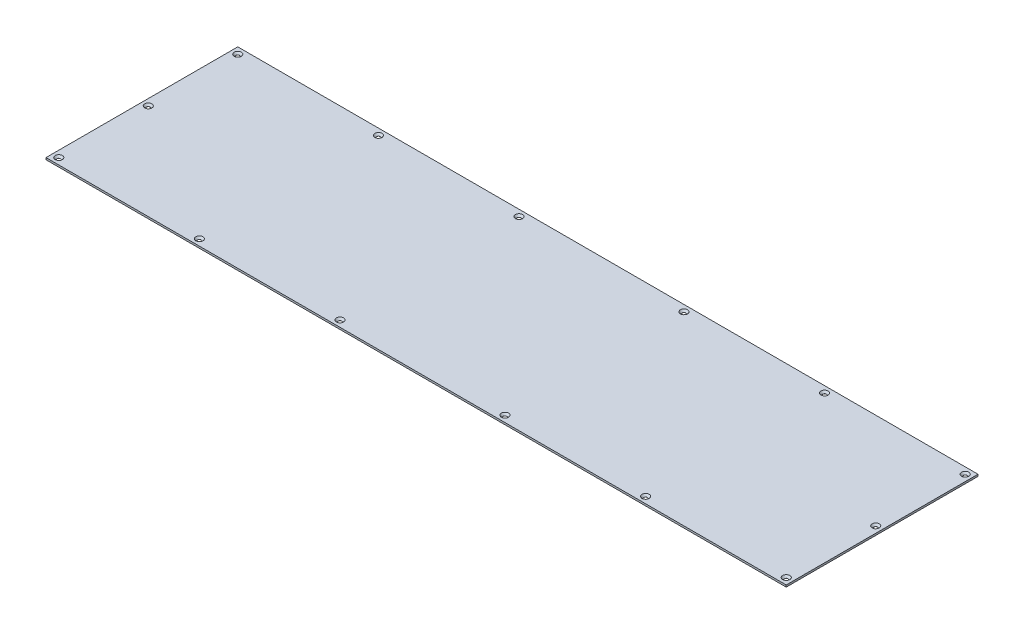
SolidWorks part; units mm, degrees
material "1060 Alloy"
ref_plane "Front Plane" through (0, 0, 0) normal (0, 0, 1) x (1, 0, 0)
ref_plane "Top Plane" through (0, 0, 0) normal (0, 1, 0) x (1, 0, 0)
ref_plane "Right Plane" through (0, 0, 0) normal (1, 0, 0) x (0, 0, -1)
sketch "Sketch1" plane through (0, 0, 0) normal (0, 1, 0) x (1, 0, 0)
  line L1 (-579, -150) -> (579, -150)
  line L2 (-579, -150) -> (-579, 150)
  line L3 (-579, 150) -> (579, 150)
  line L4 (579, -150) -> (579, 150)
  line L5 (-579, -150) -> (579, 150) construction
  line L6 (-579, 150) -> (579, -150) construction
  point P0 (0, 0)
  dimension "length" = 1158
  dimension "depth" = 300
extrude "Boss-Extrude1" add sketch "Sketch1" along normal blind 3
sketch "shelf profile projection" plane through (0, 3, 0) normal (0, 1, 0) x (1, 0, 0)
  line L0 (-579, -130) -> (-559, -150) construction
  line L1 (-579, -150) -> (-559, -150) construction
  line L2 (0, 0) -> (0, 50000) construction
  line L3 (0, 0) -> (50000, 0) construction
  line L4 (-579, -150) -> (-579, -130) construction
  line L6 (-579, -130) -> (-559, -130) construction
  line L7 (-559, -150) -> (-559, -130) construction
  line L8 (-579, -150) -> (-559, -130) construction
  line L9 (-561, -140) -> (49439, -140) construction
  line L10 (-569, -137.5) -> (-569, 49862.5) construction
  line L11 (579, 150) -> (-579, 150) construction
  line L12 (-579, 150) -> (-559, 150) construction
  line L13 (-579, 150) -> (-579, 130) construction
  line L14 (-579, 130) -> (-559, 130) construction
  line L15 (-559, 150) -> (-559, 130) construction
  line L16 (-579, 150) -> (-559, 130) construction
  line L17 (-579, 130) -> (-559, 150) construction
  line L18 (569, -137.5) -> (569, 49862.5) construction
  line L19 (-561, 140) -> (49439, 140) construction
  line L20 (-579, -150) -> (579, -150) construction
  line L21 (-559, -130) -> (-539, -130) construction
  line L22 (-559, -130) -> (-559, -150) construction
  line L23 (-559, -150) -> (-539, -150) construction
  line L24 (-539, -130) -> (-539, -150) construction
  line L25 (-579, 130) -> (-559, 110) construction
  line L26 (-579, -130) -> (-559, -130) construction
  line L27 (-579, -130) -> (-579, -110) construction
  line L28 (-579, -110) -> (-559, -110) construction
  line L29 (-559, -130) -> (-559, -110) construction
  line L30 (-579, 130) -> (-559, 130) construction
  line L31 (-579, 130) -> (-579, 110) construction
  line L32 (-579, 110) -> (-559, 110) construction
  line L33 (-559, 130) -> (-559, 110) construction
  line L34 (-559, 130) -> (-539, 130) construction
  line L35 (-559, 130) -> (-559, 150) construction
  line L36 (-559, 150) -> (-539, 150) construction
  line L37 (-539, 130) -> (-539, 150) construction
  line L38 (-559, 130) -> (-579, 110) construction
  line L39 (-559, 130) -> (-539, 150) construction
  line L40 (-559, 150) -> (-539, 130) construction
  line L41 (-579, -110) -> (-559, -130) construction
  line L42 (-579, -130) -> (-559, -110) construction
  line L43 (-559, -130) -> (-539, -150) construction
  line L44 (-539, -130) -> (-559, -150) construction
  line L45 (559, -150) -> (539, -150) construction
  line L46 (539, -130) -> (539, -150) construction
  line L47 (559, -130) -> (539, -130) construction
  line L48 (559, -150) -> (559, -130) construction
  line L49 (539, -130) -> (559, -150) construction
  line L50 (559, -130) -> (539, -150) construction
  point P11 (-569, -140)
  point P14 (-569, 140)
  dimension "shelf profile dim" = 20
  dimension "back length profile offset" = 10
sketch "hole placement" [suppressed] plane through (0, 3, 0) normal (0, 1, 0) x (1, 0, 0)
  line L0 (-579, -130) -> (-559, -150) construction
  line L1 (-539, -130) -> (-559, -150) construction
  line L2 (-559, 150) -> (-539, 130) construction
  line L3 (-200561, -140) -> (249439, -140) construction
  line L5 (539, -130) -> (559, -150) construction
  line L6 (0, -200000) -> (0, 250000) construction
  line L7 (0, -200000) -> (0, 250000) construction
  point P0 (-569, -140)
  point P1 (-569, -70)
  point P4 (-549, -140)
  point P5 (-392.1429, 140)
  point P6 (-549, 140)
  point P9 (-569, 0)
  point P13 (-569, 70)
  point P14 (-569, 140)
  point P15 (-392.1429, -140)
  point P16 (-235.2857, -140)
  point P18 (-78.4286, -140)
  point P19 (78.4286, -140)
  point P20 (235.2857, -140)
  point P21 (392.1429, -140)
  point P22 (549, -140)
  point P24 (-235.2857, 140)
  point P25 (-78.4286, 140)
  point P26 (78.4286, 140)
  point P27 (235.2857, 140)
  point P29 (392.1429, 140)
  point P32 (549, 140)
  point P35 (569, 140)
  point P36 (569, 70)
  point P37 (569, 0)
  point P38 (569, -70)
  point P39 (569, -140)
  dimension "D1" = 8
  dimension "D2" = 5
  dimension "D3" = 8
hole_wizard "Hole1" [suppressed] positions "Sketch5" profile "Sketch7" legacy
sketch "Sketch5" [suppressed] plane through (0, 3, 0) normal (0, 1, 0) x (1, 0, 0)
  point P0 (-559, -140)
  point P3 (-559, -70.625)
  point P6 (-559, -1.25)
  point P9 (-559, 68.125)
  point P12 (-559, 137.5)
  point P15 (-539, 137.5)
  point P18 (-539, -140)
  point P21 (-385, -140)
  point P24 (-385, 137.5)
  point P27 (-231, 137.5)
  point P30 (-77, 137.5)
  point P33 (-231, -140)
  point P36 (-77, -140)
  point P39 (77, -140)
  point P42 (77, 137.5)
  point P45 (231, 137.5)
  point P48 (231, -140)
  point P51 (385, -140)
  point P54 (539, -140)
  point P57 (559, -140)
  point P60 (559, -70.625)
  point P63 (559, -1.25)
  point P66 (559, 68.125)
  point P69 (559, 137.5)
  point P72 (539, 137.5)
  point P75 (385, 137.5)
sketch "Sketch7" plane through (-559, 3, 140) normal (1, 0, 0) x (0, 0, 1)
  line L0 (0, 0) -> (0, 4.6524)
  line L1 (0, 4.6524) -> (2.75, 3)
  line L2 (2.75, 3) -> (2.75, 3.1635)
  line L3 (2.75, 3.1635) -> (5.5, 0)
  line L4 (5.5, 0) -> (0, 0)
  line L5 (0, -14.3089) -> (0, 102.4216) construction
  line L6 (0, 4.6524) -> (-2.75, 3) construction
  line L7 (-2.75, 3.1635) -> (-5.5, 0) construction
  dimension "Diameter" = 5.5
  dimension "Depth" = 3
  dimension "C-Sink Diameter" = 11
  dimension "C-Sink Angle" = 82
  dimension "Drill Angle" = 118
sketch "Sketch8" [suppressed] plane through (0, 3, 0) normal (0, 1, 0) x (1, 0, 0)
  line L0 (-541, 139.5) -> (-491, 139.5) construction
  line L1 (0, 0) -> (0, 50000) construction
  line L2 (569, 150) -> (-569, 150) construction
  line L3 (-569, 150) -> (-569, -150) construction
  point P5 (-516, 139.5)
  point P10 (491, 139.5)
  point P11 (516, 139.5)
  point P12 (541, 139.5)
  dimension "D1" = 25
  dimension "D2" = 10.5
  dimension "D3" = 53
hole_wizard "Hole2" [suppressed] positions "Sketch9" profile "Sketch10" legacy
sketch "Sketch9" plane through (0, 3, 0) normal (0, 1, 0) x (1, 0, 0)
  point P0 (-541, 139.5)
  point P3 (-516, 139.5)
  point P6 (-491, 139.5)
  point P9 (491, 139.5)
  point P12 (516, 139.5)
  point P15 (541, 139.5)
sketch "Sketch10" plane through (-541, 3, -139.5) normal (1, 0, 0) x (0, 0, 1)
  line L0 (0, 0) -> (0, 4.6524)
  line L1 (0, 4.6524) -> (2.75, 3)
  line L2 (2.75, 3) -> (2.75, 3.1635)
  line L3 (2.75, 3.1635) -> (5.5, 0)
  line L4 (5.5, 0) -> (0, 0)
  line L5 (0, -14.3089) -> (0, 102.4216) construction
  line L6 (0, 4.6524) -> (-2.75, 3) construction
  line L7 (-2.75, 3.1635) -> (-5.5, 0) construction
  dimension "Diameter" = 5.5
  dimension "Depth" = 3
  dimension "C-Sink Diameter" = 11
  dimension "C-Sink Angle" = 82
  dimension "Drill Angle" = 118
sketch "Sketch11" plane through (0, 3, 0) normal (0, 1, 0) x (1, 0, 0)
  line L0 (-579, -130) -> (-559, -150) construction
  line L1 (569, -200137.5) -> (569, 249862.5) construction
  line L2 (-200000, 0) -> (250000, 0) construction
  line L3 (-200000, 0) -> (250000, 0) construction
  line L4 (0, -200000) -> (0, 250000) construction
  line L5 (0, -200000) -> (0, 250000) construction
  line L6 (579, 150) -> (-579, 150) construction
  line L7 (-579, -150) -> (579, -150) construction
  point P0 (-569, -140)
  point P1 (-349, -140)
  point P4 (-569, -140)
  point P5 (-129, -140)
  point P6 (-349, 140)
  point P7 (129, -140)
  point P8 (349, -140)
  point P9 (569, -140)
  point P10 (-129, 140)
  point P11 (-569, 0)
  point P12 (-569, 140)
  point P16 (129, 140)
  point P21 (349, 140)
  point P22 (569, 140)
  point P26 (569, 0)
  dimension "D1" = 10
  dimension "D3" = 10
  dimension "D4" = 220
  dimension "D5" = 220
  dimension "D6" = 220
  dimension "D7" = 220
  dimension "D2" = 3
hole_wizard "Hole3" positions "Sketch12" profile "Sketch13" legacy end condition through all
sketch "Sketch12" plane through (0, 3, 0) normal (0, 1, 0) x (1, 0, 0)
  point P0 (-569, -140)
  point P3 (-569, 0)
  point P6 (-569, 140)
  point P9 (-349, 140)
  point P12 (-349, -140)
  point P15 (-129, -140)
  point P18 (-129, 140)
  point P21 (129, 140)
  point P24 (129, -140)
  point P27 (349, -140)
  point P30 (349, 140)
  point P33 (569, 140)
  point P36 (569, -140)
  point P39 (569, 0)
sketch "Sketch13" plane through (-569, 3, 140) normal (1, 0, 0) x (0, 0, 1)
  line L0 (0, 0) -> (0, 4.6524)
  line L1 (0, 4.6524) -> (2.75, 3)
  line L2 (2.75, 3) -> (2.75, 2.85)
  line L3 (2.75, 2.85) -> (5.6, 0)
  line L4 (5.6, 0) -> (0, 0)
  line L5 (0, -14.3089) -> (0, 102.4216) construction
  line L6 (0, 4.6524) -> (-2.75, 3) construction
  line L7 (-2.75, 2.85) -> (-5.6, 0) construction
  dimension "Diameter" = 5.5
  dimension "Depth" = 3
  dimension "C-Sink Diameter" = 11.2
  dimension "C-Sink Angle" = 90
  dimension "Drill Angle" = 118
